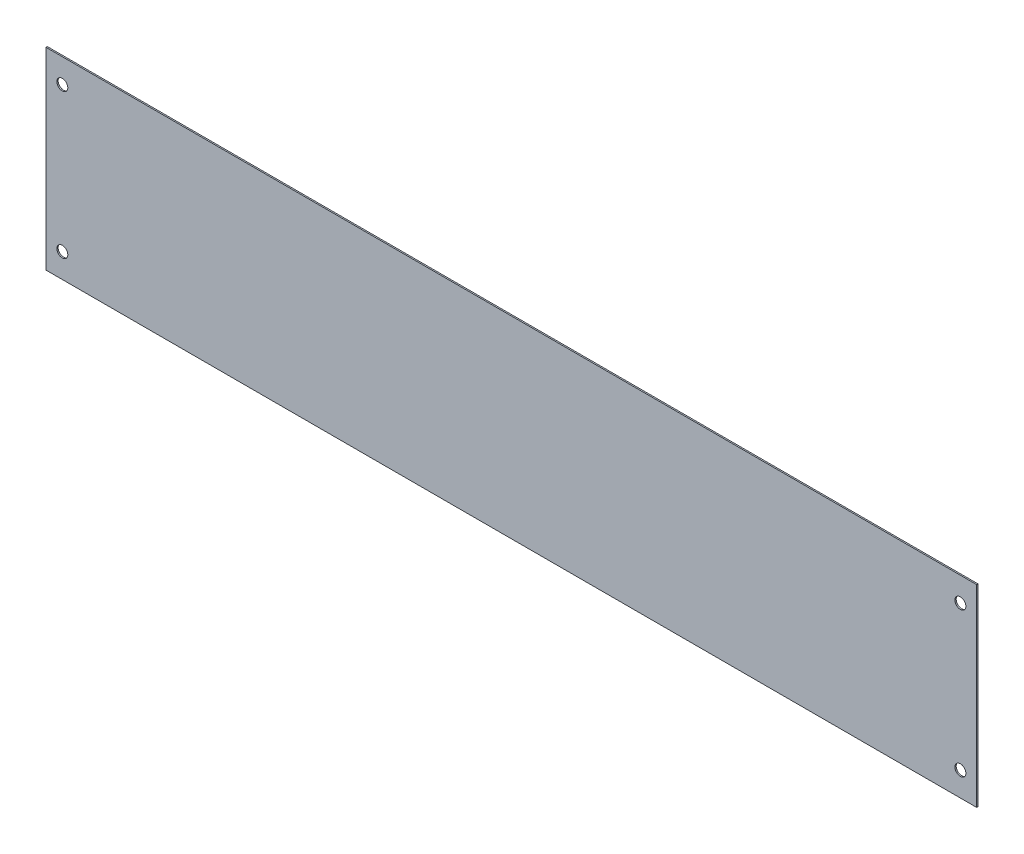
SolidWorks part; units mm, degrees
ref_plane "Спереди" through (0, 0, 0) normal (0, 0, 1) x (1, 0, 0)
ref_plane "Сверху" through (0, 0, 0) normal (0, 1, 0) x (1, 0, 0)
ref_plane "Справа" through (0, 0, 0) normal (1, 0, 0) x (0, 0, -1)
other "Configuration Table"
sketch "Эскиз1" plane through (0, 0, 0) normal (0, 0, 1) x (1, 0, 0)
  line L0 (5.4, 82.2) -> (11.4, 82.2) construction
  line L1 (0, 88.1) -> (482.2, 88.1)
  line L2 (0, 88.1) -> (0, 0)
  line L3 (0, 0) -> (482.2, 0)
  line L4 (482.2, 88.1) -> (482.2, 0)
  line L5 (5.4, 86.2) -> (11.4, 86.2)
  line L6 (5.4, 78.2) -> (11.4, 78.2)
  line L7 (5.4, 5.9) -> (11.4, 5.9) construction
  line L8 (5.4, 9.9) -> (11.4, 9.9)
  line L9 (5.4, 1.9) -> (11.4, 1.9)
  line L10 (470.8, 5.9) -> (476.8, 5.9) construction
  line L11 (470.8, 9.9) -> (476.8, 9.9)
  line L12 (470.8, 1.9) -> (476.8, 1.9)
  line L13 (470.8, 82.2) -> (476.8, 82.2) construction
  line L14 (470.8, 86.2) -> (476.8, 86.2)
  line L15 (470.8, 78.2) -> (476.8, 78.2)
  line L16 (241.1, 88.1) -> (241.1, 0) construction
  line L17 (28.65, 88.1) -> (453.55, 88.1)
  line L18 (28.65, 88.1) -> (28.65, 0)
  line L19 (28.65, 0) -> (453.55, 0)
  line L20 (453.55, 88.1) -> (453.55, 0)
  line L21 (28.65, 44.05) -> (453.55, 44.05) construction
  arc A0 (5.4, 86.2) -> (5.4, 78.2) centre (5.4, 82.2) ccw
  arc A1 (11.4, 78.2) -> (11.4, 86.2) centre (11.4, 82.2) ccw
  arc A2 (5.4, 9.9) -> (5.4, 1.9) centre (5.4, 5.9) ccw
  arc A3 (11.4, 1.9) -> (11.4, 9.9) centre (11.4, 5.9) ccw
  arc A4 (470.8, 9.9) -> (470.8, 1.9) centre (470.8, 5.9) ccw
  arc A5 (476.8, 1.9) -> (476.8, 9.9) centre (476.8, 5.9) ccw
  arc A6 (470.8, 86.2) -> (470.8, 78.2) centre (470.8, 82.2) ccw
  arc A7 (476.8, 78.2) -> (476.8, 86.2) centre (476.8, 82.2) ccw
  circle A8 centre (36.1, 77.05) radius 2.5
  circle A9 centre (446.1, 77.05) radius 2.5
  circle A10 centre (446.1, 11.05) radius 2.5
  circle A11 centre (36.1, 11.05) radius 2.5
  point P7 (8.4, 82.2)
  point P15 (8.4, 5.9)
  point P23 (473.8, 5.9)
  point P30 (473.8, 82.2)
  point P41 (0, 0)
  point P42 (446.1, 13.3831)
  dimension "D14" = 5
  dimension "D1" = 482.2
  dimension "D2" = 88.1
  dimension "D3" = 8
  dimension "D4" = 6
  dimension "D5" = 5.9
  dimension "D6" = 8.4
  dimension "D7" = 8.4
  dimension "D8" = 5.9
  dimension "D9" = 8.4
  dimension "D10" = 5.9
  dimension "D11" = 8.4
  dimension "D12" = 5.9
  dimension "D13" = 424.9
  dimension "D17" = 410
  dimension "D18" = 66
  dimension "D15" = 2
  dimension "D16" = 2
extrude "Бобышка-Вытянуть1" add sketch "Эскиз1" along normal blind 0.6 contours L20 L1 L18 L3 A11 A10 A9 A8
